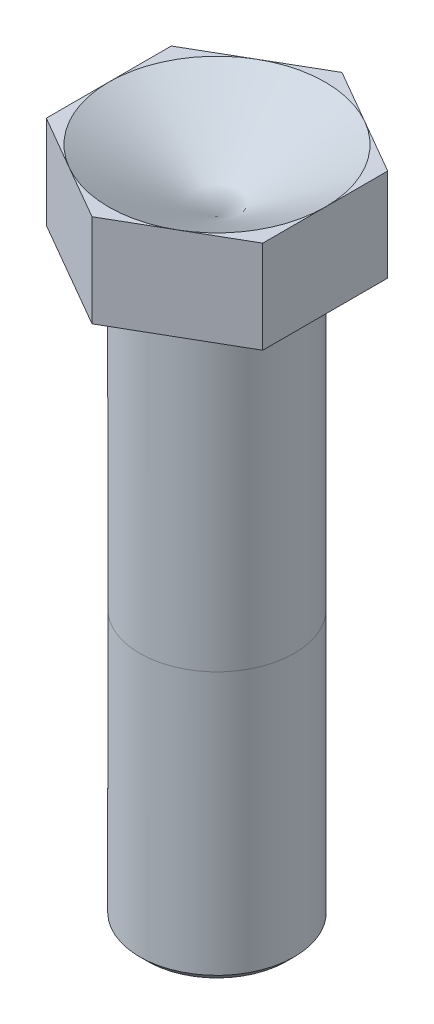
SolidWorks part; units mm, degrees
material "Alloy Steel"
ref_plane "Front Plane" through (0, 0, 0) normal (0, 0, 1) x (1, 0, 0)
ref_plane "Top Plane" through (0, 0, 0) normal (0, 1, 0) x (1, 0, 0)
ref_plane "Right Plane" through (0, 0, 0) normal (1, 0, 0) x (0, 0, -1)
sketch "Sketch1" plane through (0, 0, 0) normal (0, 1, 0) x (1, 0, 0)
  line L1 (14, 8.0829) -> (0, 16.1658)
  line L2 (0, 16.1658) -> (-14, 8.0829)
  line L3 (-14, 8.0829) -> (-14, -8.0829)
  line L4 (-14, -8.0829) -> (0, -16.1658)
  line L5 (0, -16.1658) -> (14, -8.0829)
  line L6 (14, -8.0829) -> (14, 8.0829)
  circle A0 centre (0, 0) radius 14 construction
  dimension "D1" = 28
extrude "Boss-Extrude1" add sketch "Sketch1" along normal blind 12
sketch "Sketch2" plane through (0, 12, 0) normal (0, 1, 0) x (1, 0, 0)
  line L0 (14, 8.0829) -> (0, 16.1658) construction
  circle A0 centre (0, 0) radius 14
extrude "Cut-Extrude1" cut sketch "Sketch2" against normal blind 12 draft 60
sketch "Sketch3" plane through (0, 0, 0) normal (0, -1, 0) x (1, 0, 0)
  circle A0 centre (0, 0) radius 10
  dimension "D1" = 20
extrude "Boss-Extrude2" add sketch "Sketch3" along normal blind 75
chamfer "Chamfer1" distance 1 angle 45 1 edges at (0, -75, -10)
sketch "Sketch4" plane through (0, 0, 0) normal (0, 0, 1) x (1, 0, 0)
  line L0 (-10, -40) -> (10, -40)
  line L1 (-10, 0) -> (-10, -74) construction
  line L2 (10, -74) -> (10, 0) construction
  line L3 (-10, 0) -> (10, 0) construction
  dimension "D1" = 40
split line "Split Line1"
